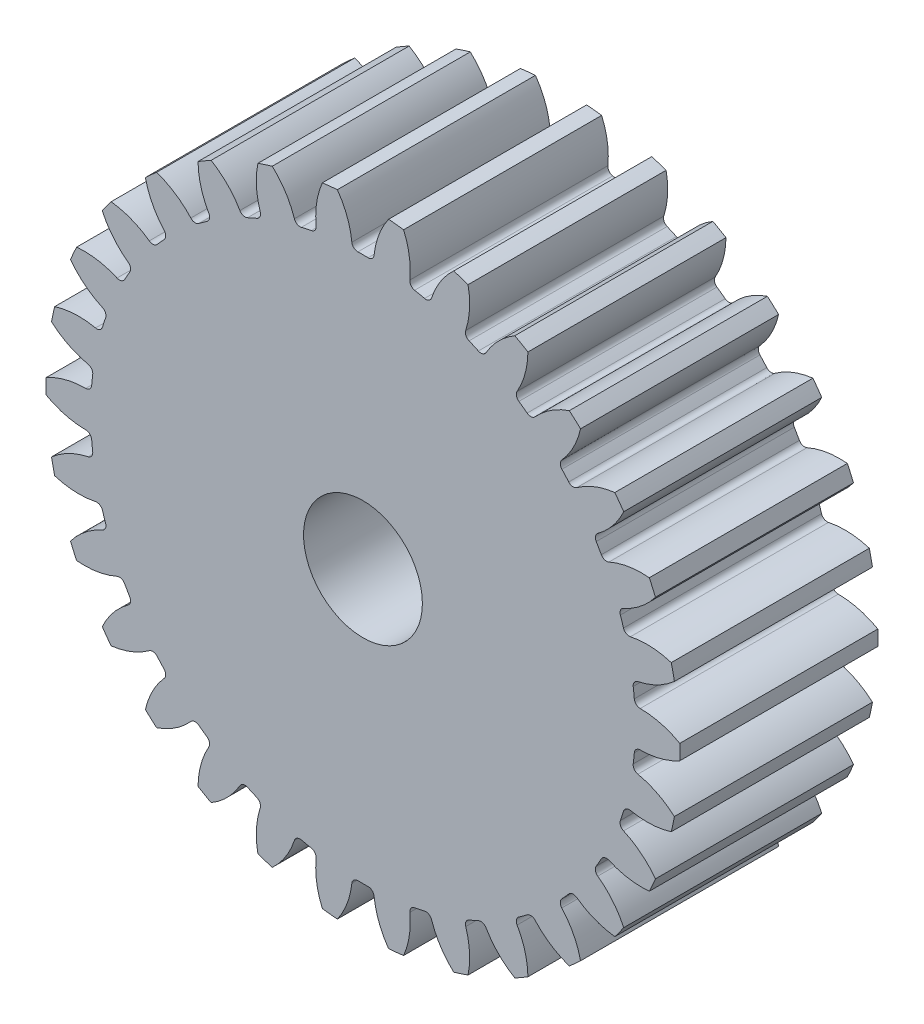
SolidWorks part; units mm, degrees
ref_plane "Płaszczyzna przednia" through (0, 0, 0) normal (0, 0, 1) x (1, 0, 0)
ref_plane "Płaszczyzna górna" through (0, 0, 0) normal (0, 1, 0) x (1, 0, 0)
ref_plane "Płaszczyzna prawa" through (0, 0, 0) normal (1, 0, 0) x (0, 0, -1)
sketch "Sketch1" plane through (0, 0, 0) normal (0, 0, 1) x (1, 0, 0)
  circle A0 centre (0, 0) radius 30
  circle A1 centre (0, 0) radius 32
  circle A2 centre (0, 0) radius 27.5
  circle A3 centre (0, 0) radius 6
  dimension "D1" = 60
  dimension "D2" = 64
  dimension "D3" = 4.5
  dimension "D4" = 12
extrude "Boss-Extrude1" add sketch "Sketch1" along normal mid plane 20 contours A1
sketch "Sketch2" plane through (0, 0, 0) normal (0, 0, 1) x (1, 0, 0)
  line L0 (0, 0) -> (0, 32) construction
  line L1 (-1.5701, 29.9589) -> (1.5701, 29.9589) construction
  line L2 (0, 0) -> (-1.0822, 27.4787) construction
  line L3 (0, 25.6451) -> (-2.6385, 32.8944) construction
  line L4 (0, 0) -> (3.3449, 31.8247) construction
  line L5 (1.5701, 29.9589) -> (4.693, 29.6307) construction
  circle A0 centre (0, 0) radius 32 construction
  arc A1 (-3.3568, 32.8288) -> (-1.0822, 27.4787) centre (-9.2704, 27.1562) cw
  arc A2 (3.3568, 32.8288) -> (1.0822, 27.4787) centre (9.2704, 27.1562) ccw
  circle A3 centre (0, 0) radius 27.5 construction
  arc A4 (1.0822, 27.4787) -> (-1.0822, 27.4787) centre (0, 0) ccw
  circle A8 centre (0, 0) radius 33
  arc A9 (3.3568, 32.8288) -> (-3.3568, 32.8288) centre (0, 0) ccw
  circle A10 centre (0, 0) radius 30 construction
  circle A11 centre (0, 0) radius 32 construction
  circle A12 centre (0, 0) radius 6 construction
  circle A13 centre (0, 0) radius 6
  dimension "D2" = 20
  dimension "D3" = 6
  dimension "D1" = 1
extrude "Cut-Extrude1" cut sketch "Sketch2" against normal through all both and the other way through all contours A9 A1 A4 A2 | A13
fillet "Fillet1" radius 0.6 2 edges at (1.0822, 27.4787, 0) (-1.0822, 27.4787, 0)
pattern_circular "CirPattern1" count 30 over 360 about axis through (0, 0, 0) along (0, 0, 1) of "Cut-Extrude1", "Fillet1"
equation "\"Module\"= 2mm'Modół"
equation "\"Number of Teeth\"= 30'Liczba zębów"
equation "\"D1@Sketch1\"=\"Module\"*\"Number of Teeth\""
equation "\"D2@Sketch1\"=(\"Number of Teeth\"+2) * \"Module\""
equation "\"D3@Sketch1\"=\"Module\" * if( \"Module\"=>1.25,2.25,2.4)"
equation "\"D3@Sketch2\"=180 / \"Number of Teeth\""
equation "\"D1@Fillet1\"=.3 * \"Module\""
equation "\"D1@CirPattern1\"=\"Number of Teeth\""
equation "\"D4@Sketch1\"=(\"Module\"* \"Number of Teeth\") / 5"
